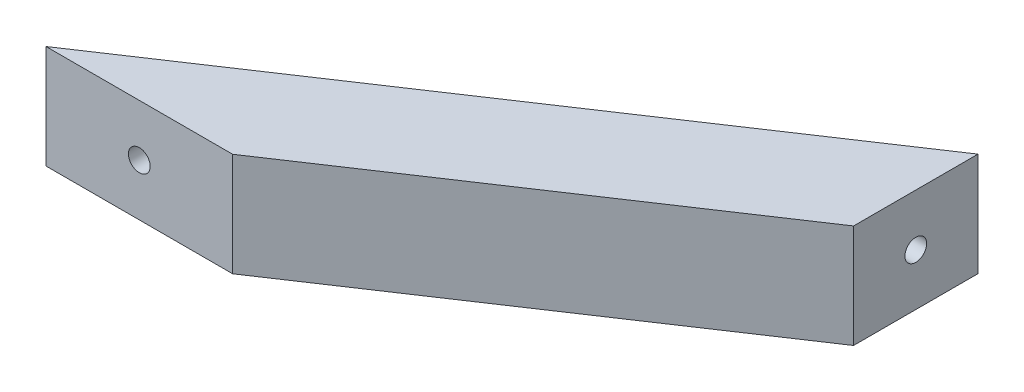
SolidWorks part; units mm, degrees
ref_plane "前视基准面" through (0, 0, 0) normal (0, 0, 1) x (1, 0, 0)
ref_plane "上视基准面" through (0, 0, 0) normal (0, 1, 0) x (1, 0, 0)
ref_plane "右视基准面" through (0, 0, 0) normal (1, 0, 0) x (0, 0, -1)
sketch "草图1" plane through (0, 0, 0) normal (0, 1, 0) x (1, 0, 0)
  line L0 (0, 0) -> (90, 0) construction
  line L1 (90, 0) -> (90, 60) construction
  line L2 (90, 60) -> (0, 0)
  line L3 (90, 72.0185) -> (-18.0278, 0)
  line L4 (90, 47.9815) -> (18.0278, 0)
  line L5 (84.453, 68.3205) -> (-5.547, 8.3205) construction
  line L6 (95.547, 51.6795) -> (5.547, -8.3205) construction
  line L7 (-18.0278, 0) -> (18.0278, 0)
  line L8 (90, 72.0185) -> (90, 47.9815)
  dimension "D1" = 90
  dimension "D2" = 60
  dimension "D3" = 10
  dimension "D4" = 10
extrude "凸台-拉伸1" add sketch "草图1" along normal blind 20 contours L8 L2 L7 L4
sketch "草图2" plane through (90, 0, 0) normal (1, 0, 0) x (0, 0, -1)
  line L0 (47.9815, 20) -> (72.0185, 0) construction
  line L1 (72.0185, 20) -> (47.9815, 0) construction
  line L2 (72.0185, 0) -> (47.9815, 0) construction
  line L3 (47.9815, 20) -> (47.9815, 0) construction
  circle A0 centre (60, 10) radius 2.1
  dimension "D1" = 4.2
sketch "草图4" plane through (-5.547, 0, -8.3205) normal (-0.5547, 0, -0.8321) x (-0.8321, 0, 0.5547)
  line L0 (-101.4999, 20) -> (-114.8332, 0) construction
  line L1 (-114.8332, 20) -> (-114.8332, 0) construction
  circle A0 centre (-108.1665, 10) radius 2.1
  dimension "D1" = 6.6667
  dimension "D2" = 4.2
sketch "草图5" plane through (0, 0, 0) normal (0, 0, 1) x (1, 0, 0)
  line L0 (-18.0278, 20) -> (18.0278, 0) construction
  line L1 (-18.0278, 0) -> (18.0278, 20) construction
extrude "切除-拉伸2" cut sketch "草图2" against normal through all
sketch "草图6" plane through (0, 0, 0) normal (0, 0, 1) x (1, 0, 0)
  line L0 (-18.0278, 20) -> (18.0278, 0) construction
  circle A0 centre (0, 10) radius 2.1
  dimension "D1" = 4.2
extrude "切除-拉伸3" cut sketch "草图6" against normal through all
